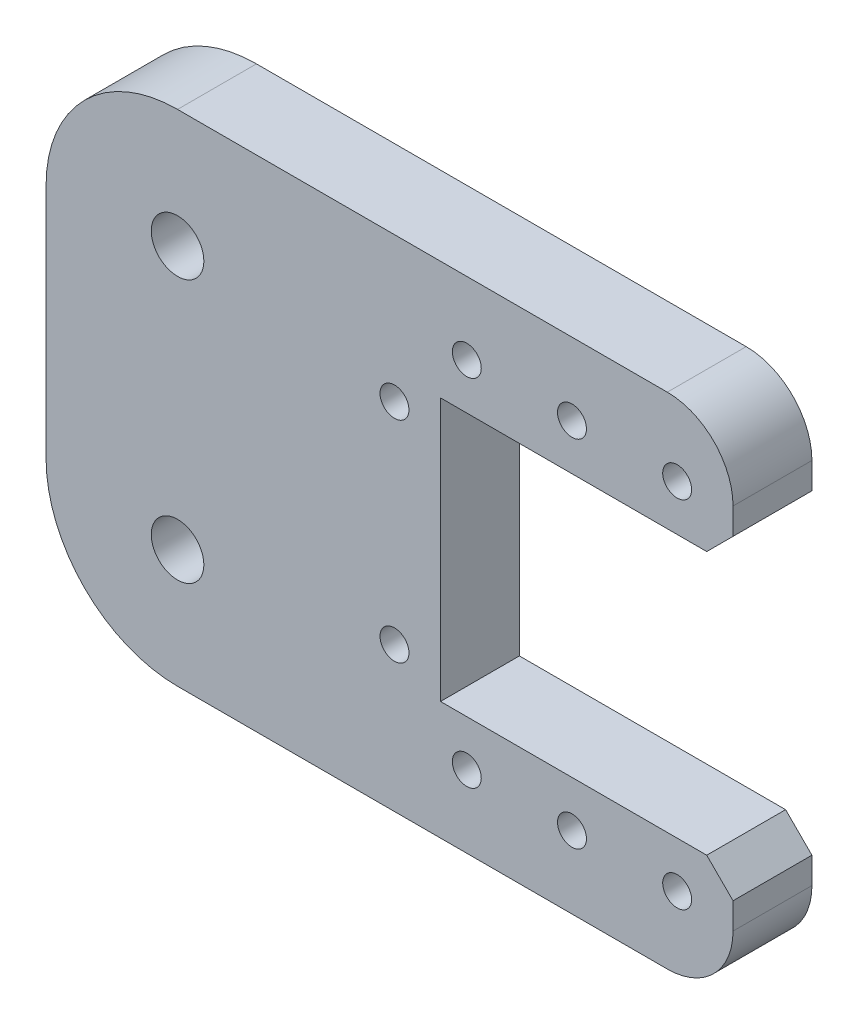
SolidWorks part; units mm, degrees
ref_plane "Plan de face" through (0, 0, 0) normal (0, 0, 1) x (1, 0, 0)
ref_plane "Plan de dessus" through (0, 0, 0) normal (0, 1, 0) x (1, 0, 0)
ref_plane "Plan de droite" through (0, 0, 0) normal (1, 0, 0) x (0, 0, -1)
sketch "Esquisse1" plane through (0, 0, 0) normal (0, 0, 1) x (1, 0, 0)
  line L0 (-36.0819, 9.1835) -> (-36.0819, -28.8165)
  line L1 (-36.0819, -28.8165) -> (16.1681, -28.8165)
  line L2 (16.1681, -28.8165) -> (16.1681, -19.8165)
  line L3 (16.1681, -19.8165) -> (-6.0819, -19.8165)
  line L4 (-6.0819, -19.8165) -> (-6.0819, 0.1835)
  line L5 (-6.0819, 0.1835) -> (16.1681, 0.1835)
  line L6 (16.1681, 0.1835) -> (16.1681, 9.1835)
  line L7 (16.1681, 9.1835) -> (-36.0819, 9.1835)
  line L8 (-16.0819, 9.1835) -> (-16.0819, -28.8165) construction
  line L9 (-26.0819, 9.1835) -> (-26.0819, -28.8165) construction
  circle A0 centre (-26.0819, 0.1835) radius 2
  circle A1 centre (-26.0819, -19.8165) radius 2
  dimension "D8" = 4
  dimension "D9" = 4
  dimension "D1" = 9
  dimension "D2" = 20
  dimension "D3" = 9
  dimension "D4" = 22.25
  dimension "D5" = 52.25
  dimension "D6" = 20
  dimension "D7" = 10
extrude "Boss.-Extru.1" add sketch "Esquisse1" along normal blind 6
fillet "Congé1" radius 10 2 edges at (-36.0819, -28.8165, 3) (-36.0819, 9.1835, 3)
fillet "Congé2" radius 5 2 edges at (16.1681, -28.8165, 3) (16.1681, 9.1835, 3)
chamfer "Chanfrein1" distance 2 angle 45 2 edges at (16.1681, -19.8165, 3) (16.1681, 0.1835, 3)
sketch "Esquisse2" plane through (0, 0, 6) normal (0, 0, 1) x (1, 0, 0)
  circle A0 centre (-4.0819, 3.6835) radius 1.1
  circle A1 centre (3.9181, 3.6835) radius 1.1
  circle A2 centre (11.9181, 3.6835) radius 1.1
  circle A3 centre (-9.5819, -1.8165) radius 1.1
  circle A4 centre (-9.5819, -17.8165) radius 1.1
  circle A5 centre (-4.0819, -23.3165) radius 1.1
  circle A6 centre (3.9181, -23.3165) radius 1.1
  circle A7 centre (11.9181, -23.3165) radius 1.1
extrude "Enlèv. mat.-Extru.1" cut sketch "Esquisse2" against normal blind 6
